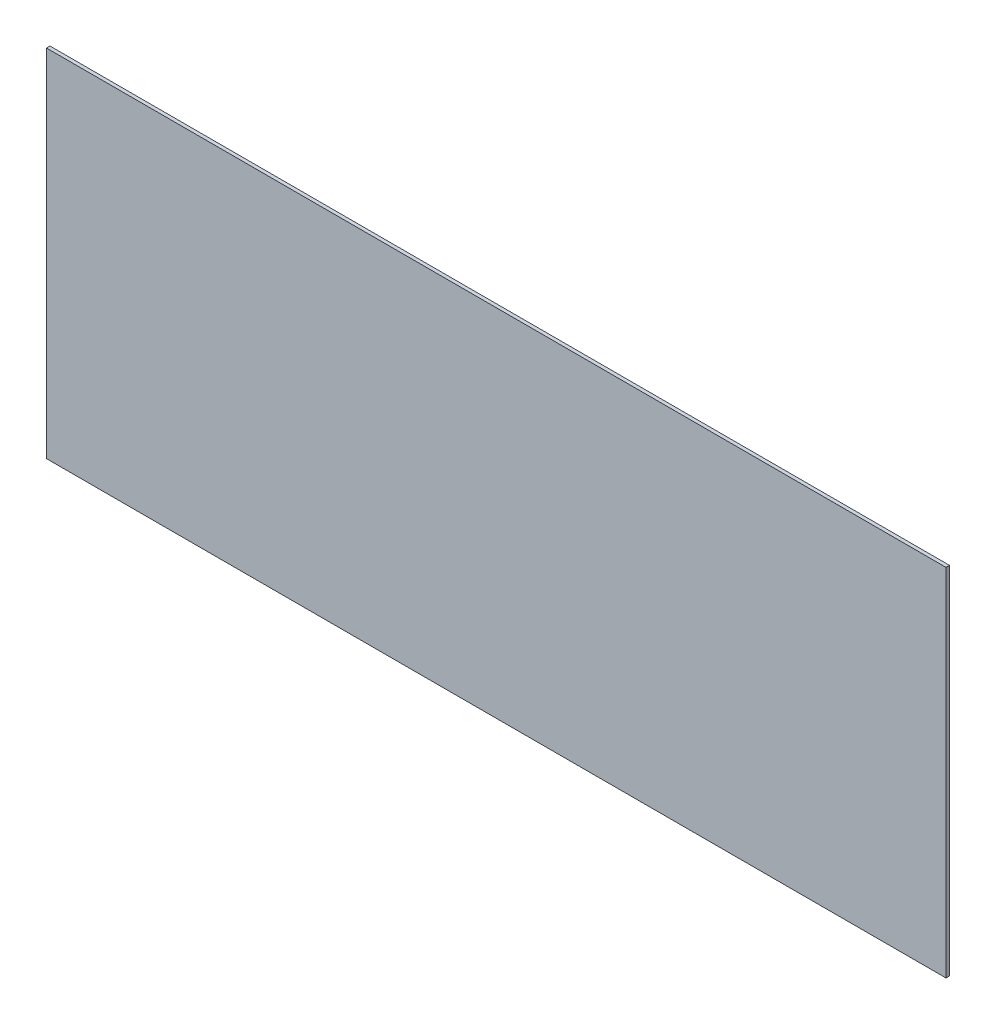
SolidWorks part; units mm, degrees
material "ﾎﾟﾘｴﾁﾚﾝﾃﾚﾌﾀﾗｰﾄ(PET)"
ref_plane "正面" through (0, 0, 0) normal (0, 0, 1) x (1, 0, 0)
ref_plane "平面" through (0, 0, 0) normal (0, 1, 0) x (1, 0, 0)
ref_plane "右側面" through (0, 0, 0) normal (1, 0, 0) x (0, 0, -1)
sketch "ｽｹｯﾁ1" plane through (0, 0, 0) normal (0, 0, 1) x (1, 0, 0)
  line L1 (64.5, -25.5) -> (-64.5, -25.5)
  line L2 (64.5, -25.5) -> (64.5, 25.5)
  line L3 (64.5, 25.5) -> (-64.5, 25.5)
  line L4 (-64.5, -25.5) -> (-64.5, 25.5)
  line L5 (64.5, -25.5) -> (-64.5, 25.5) construction
  line L6 (64.5, 25.5) -> (-64.5, -25.5) construction
  point P0 (0, 0)
  dimension "D1" = 129
  dimension "D2" = 51
extrude "ﾎﾞｽ - 押し出し1" add sketch "ｽｹｯﾁ1" along normal blind 0.5
